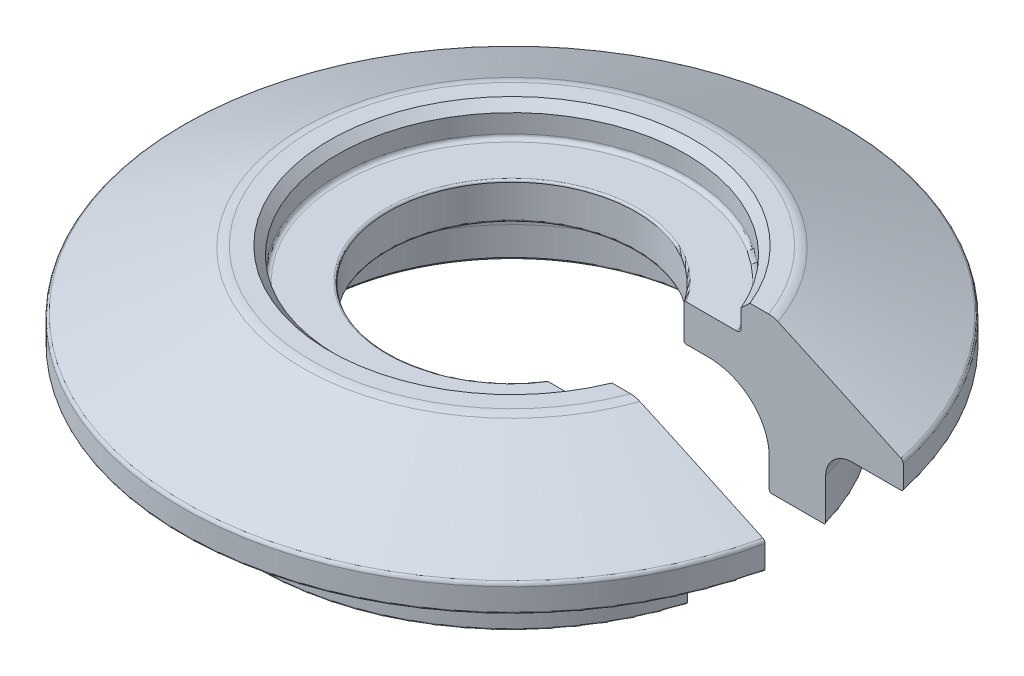
SolidWorks part; units mm, degrees
material "6061-T6 (SS)"
ref_plane "Front Plane" through (0, 0, 0) normal (0, 0, 1) x (1, 0, 0)
ref_plane "Top Plane" through (0, 0, 0) normal (0, 1, 0) x (1, 0, 0)
ref_plane "Right Plane" through (0, 0, 0) normal (1, 0, 0) x (0, 0, -1)
sketch "Sketch23" plane through (0, 0, 0) normal (0, 0, 1) x (1, 0, 0)
  line L0 (0, -46.91) -> (0, -156.1308) construction
  line L1 (15.3924, -4.572) -> (15.3924, 0)
  line L2 (15.3924, 0) -> (21.6535, 0)
  line L3 (21.6535, 0) -> (21.6535, 3.81)
  line L4 (21.6535, 3.81) -> (25.4, 3.81)
  line L5 (25.4, 3.81) -> (40.9194, -3.6322)
  line L6 (40.9194, -3.6322) -> (40.9194, -6.9342)
  line L7 (40.9194, -6.9342) -> (34.7345, -6.9342)
  line L8 (31.5595, -10.1092) -> (31.5595, -15.3162)
  line L9 (31.5595, -15.3162) -> (24.892, -15.3162)
  line L10 (17.9324, -4.572) -> (15.3924, -4.572)
  line L11 (24.892, -11.5316) -> (24.892, -15.3162)
  arc A0 (34.7345, -6.9342) -> (31.5595, -10.1092) centre (34.7345, -10.1092) ccw
  arc A1 (24.892, -11.5316) -> (17.9324, -4.572) centre (17.9324, -11.5316) ccw
  dimension "D1" = 30.7848
  dimension "D13" = 3.175
  dimension "D2" = 81.8388
  dimension "D3" = 50.8
  dimension "D4" = 43.307
  dimension "D5" = 63.119
  dimension "D6" = 49.784
  dimension "D7" = 3.81
  dimension "D8" = 4.572
  dimension "D9" = 19.1262
  dimension "D10" = 8.382
  dimension "D11" = 3.302
  dimension "D12" = 2.54
revolve "Revolve3" add sketch "Sketch23" angle 360 about L0
fillet "Fillet1" radius 0.254 3 edges at (-15.3924, 0, 0) (-15.3924, -4.572, 0) (-24.892, -15.3162, 0)
chamfer "Chamfer1" distance 1.016 angle 45 1 edges at (-21.6535, 3.81, 0)
fillet "Fillet2" radius 0.508 1 edges at (-21.6535, 0, 0)
fillet "Fillet3" radius 2.54 1 edges at (-25.4, 3.81, 0)
fillet "Fillet4" radius 0.508 1 edges at (-40.9194, -3.6322, 0)
fillet "Fillet5" radius 0.254 2 edges at (-40.9194, -6.9342, 0) (-31.5595, -15.3162, 0)
sketch "Sketch24" plane through (0, 0, 0) normal (0, 1, 0) x (1, 0, 0)
  line L1 (0, 8.5725) -> (40.9194, 8.5725)
  line L2 (0, 8.5725) -> (0, -8.5725)
  line L3 (0, -8.5725) -> (40.9194, -8.5725)
  line L4 (40.9194, 8.5725) -> (40.9194, -8.5725)
  circle A0 centre (0, 0) radius 40.9194 construction
  dimension "D1" = 17.145
extrude "Cut-Extrude1" cut sketch "Sketch24" against normal through all both and the other way through all
